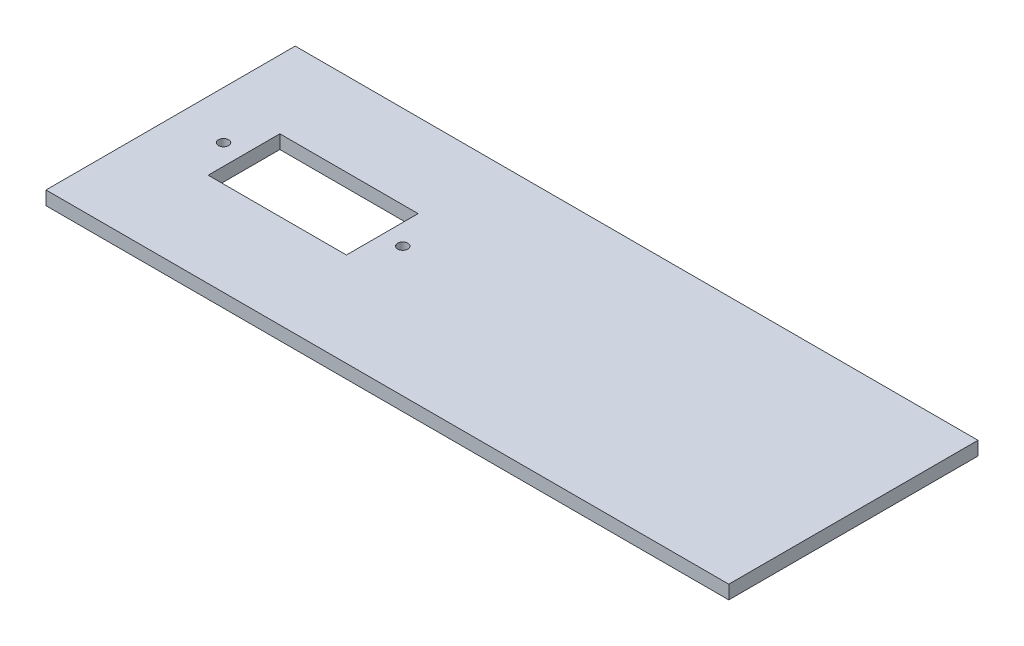
SolidWorks part; units mm, degrees
ref_plane "Front Plane" through (0, 0, 0) normal (0, 0, 1) x (1, 0, 0)
ref_plane "Top Plane" through (0, 0, 0) normal (0, 1, 0) x (1, 0, 0)
ref_plane "Right Plane" through (0, 0, 0) normal (1, 0, 0) x (0, 0, -1)
sketch "Sketch1" plane through (0, 0, 0) normal (1, 0, 0) x (0, 0, -1)
  line L1 (36.5, -2) -> (-36.5, -2)
  line L2 (36.5, -2) -> (36.5, 2)
  line L3 (36.5, 2) -> (-36.5, 2)
  line L4 (-36.5, -2) -> (-36.5, 2)
  line L5 (36.5, -2) -> (-36.5, 2) construction
  line L6 (36.5, 2) -> (-36.5, -2) construction
  point P0 (0, 0)
  dimension "D1" = 4
  dimension "D2" = 73
extrude "Boss-Extrude1" add sketch "Sketch1" against normal blind 200
sketch "Sketch2" plane through (0, 2, 0) normal (0, 1, 0) x (1, 0, 0)
  line L0 (-200, -36.5) -> (0, -36.5) construction
  line L1 (-180, 12) -> (-139.5, 12)
  line L2 (-180, 12) -> (-180, -9)
  line L3 (-180, -9) -> (-139.5, -9)
  line L4 (-139.5, 12) -> (-139.5, -9)
  line L5 (-180, 12) -> (-139.5, -9) construction
  line L6 (-180, -9) -> (-139.5, 12) construction
  line L7 (-200, 36.5) -> (-200, -36.5) construction
  line L8 (-159.75, 1.5) -> (-159.75, -9) construction
  line L9 (-200, 36.5) -> (0, 36.5) construction
  circle A0 centre (-186, 1.5) radius 1.5
  circle A1 centre (-133.5, 1.5) radius 1.5
  point P0 (-159.75, 1.5)
  dimension "D5" = 3
  dimension "D1" = 21
  dimension "D2" = 40.5
  dimension "D3" = 38
  dimension "D4" = 20
  dimension "D6" = 6
  dimension "D7" = 38
extrude "Cut-Extrude1" cut sketch "Sketch2" against normal blind 2000
